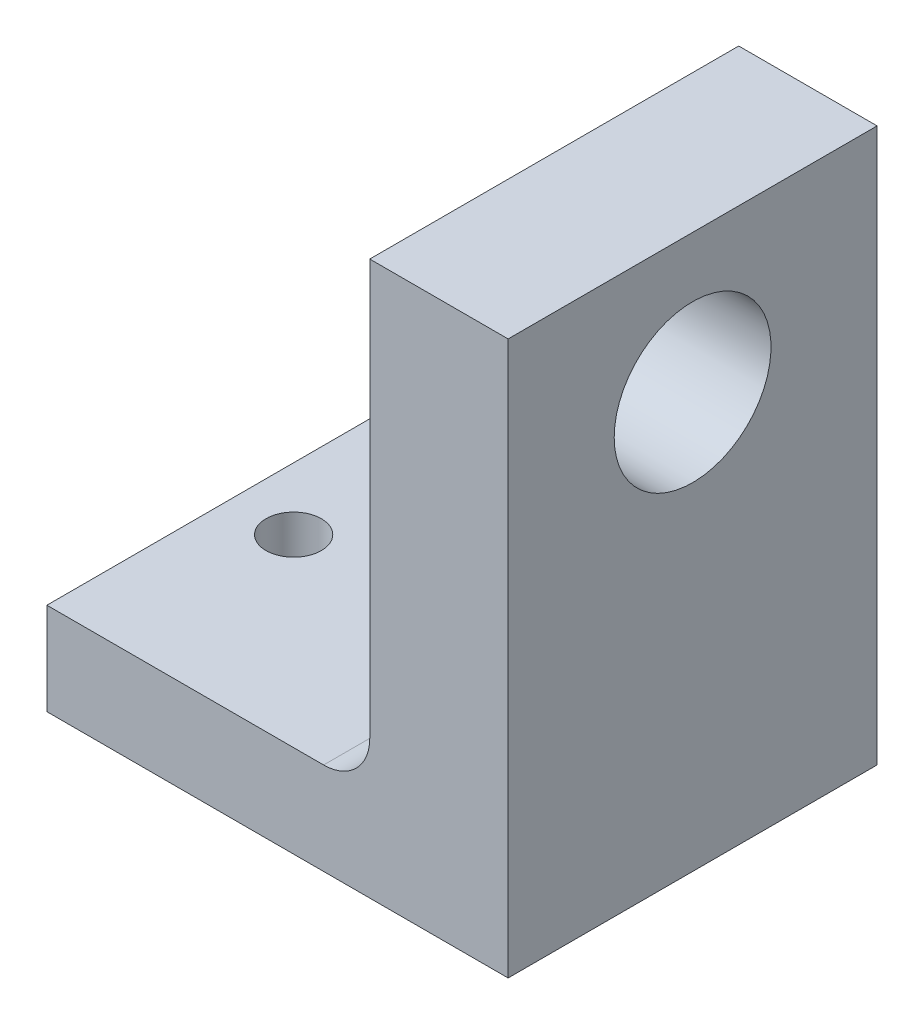
SolidWorks part; units mm, degrees
ref_plane "正面" through (0, 0, 0) normal (0, 0, 1) x (1, 0, 0)
ref_plane "平面" through (0, 0, 0) normal (0, 1, 0) x (1, 0, 0)
ref_plane "右側面" through (0, 0, 0) normal (1, 0, 0) x (0, 0, -1)
sketch "ｽｹｯﾁ1" plane through (0, 0, 0) normal (0, 0, 1) x (1, 0, 0)
  line L0 (-5, -6) -> (5, -6)
  line L1 (5, -6) -> (5, 6)
  line L2 (5, 6) -> (2, 6)
  line L3 (2, 6) -> (2, -4)
  line L4 (2, -4) -> (-5, -4)
  line L5 (-5, -4) -> (-5, -6)
  point P2 (0, -6)
  point P7 (5, 0)
  dimension "D1" = 2
  dimension "D2" = 10
  dimension "D3" = 10
  dimension "D4" = 3
extrude "ﾎﾞｽ - 押し出し1" add sketch "ｽｹｯﾁ1" along normal blind 8
sketch "ｽｹｯﾁ2" plane through (0, -4, 0) normal (0, 1, 0) x (1, 0, 0)
  line L0 (-5, -8) -> (-5, 0) construction
  line L2 (-4.25, -4) -> (-5, -4) construction
  circle A0 centre (-1.11, -4) radius 0.6
  circle A1 centre (-3.65, -4) radius 0.6
  point P5 (-5, -4)
  dimension "D1" = 1.2
  dimension "D2" = 2.54
  dimension "D3" = 0.75
extrude "ｶｯﾄ - 押し出し1" cut sketch "ｽｹｯﾁ2" against normal through all
hole_wizard "M3 すきま穴1" positions "ｽｹｯﾁ4" profile "ｽｹｯﾁ5" hole size "M3" standard "JIS" end condition through all
sketch "ｽｹｯﾁ4" plane through (2, 0, 0) normal (-1, 0, 0) x (0, 0, 1)
  line L0 (8, 6) -> (0, 6) construction
  point P0 (4, 3)
  point P5 (4, 6)
  dimension "D1" = 3
sketch "ｽｹｯﾁ5" plane through (2, 3, 4) normal (0, 1, 0) x (0, 0, 1)
  line L0 (0, 0) -> (0, 3)
  line L1 (0, 3) -> (1.7, 3)
  line L2 (1.7, 3) -> (1.7, 0)
  line L5 (1.7, 0) -> (0, 0)
  line L11 (0, -6.35) -> (0, 107.95) construction
  dimension "通し穴の直径" = 3.4
  dimension "通し穴の深さ" = 3
fillet "ﾌｨﾚｯﾄ1" radius 1 1 edges at (2, -4, 4)
